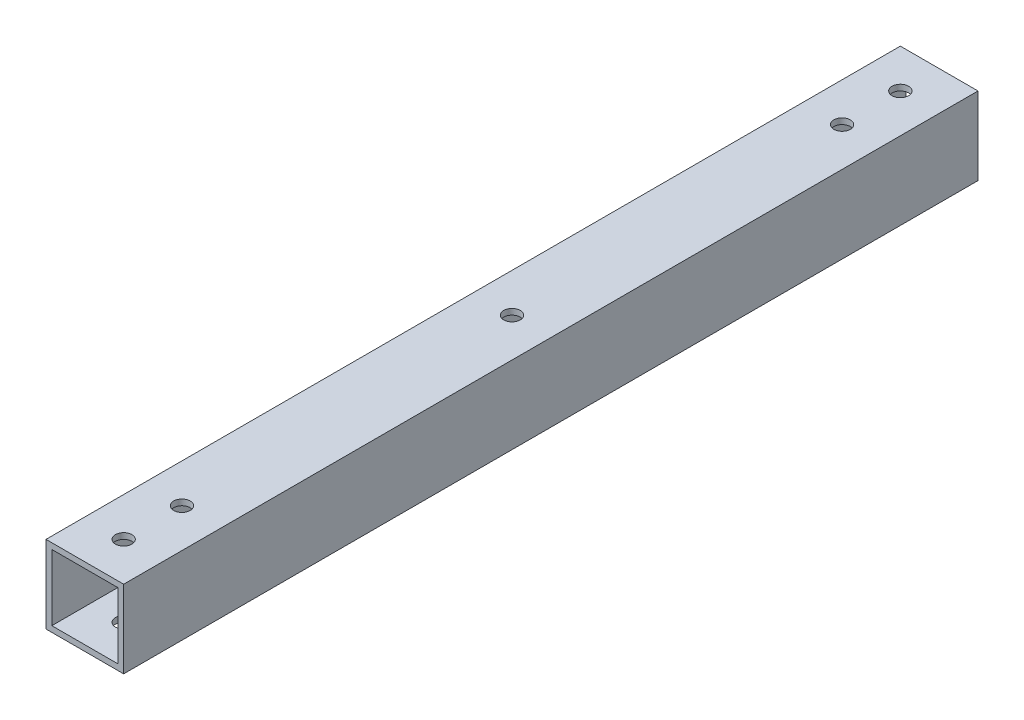
SolidWorks part; units mm, degrees
ref_plane "Front Plane" through (0, 0, 0) normal (0, 0, 1) x (1, 0, 0)
ref_plane "Top Plane" through (0, 0, 0) normal (0, 1, 0) x (1, 0, 0)
ref_plane "Right Plane" through (0, 0, 0) normal (1, 0, 0) x (0, 0, -1)
sketch "Sketch1" plane through (0, 0, 0) normal (0, 0, 1) x (1, 0, 0)
  line L0 (-8.5, -8.5) -> (8.5, -8.5)
  line L1 (-10, -10) -> (10, -10)
  line L2 (-10, -10) -> (-10, 10)
  line L3 (-10, 10) -> (10, 10)
  line L4 (10, -10) -> (10, 10)
  line L5 (-10, -10) -> (10, 10) construction
  line L6 (-10, 10) -> (10, -10) construction
  line L7 (8.5, -8.5) -> (8.5, 8.5)
  line L8 (-8.5, 8.5) -> (8.5, 8.5)
  line L9 (-8.5, -8.5) -> (-8.5, 8.5)
  point P0 (0, 0)
  dimension "D1" = 20
  dimension "D3" = 20
  dimension "D2" = 1.5
extrude "Boss-Extrude1" add sketch "Sketch1" against normal blind 220
sketch "Sketch2" plane through (0, 10, 0) normal (0, 1, 0) x (1, 0, 0)
  line L0 (10, 0) -> (-10, 0) construction
  line L1 (-10, 110) -> (10, 110) construction
  line L2 (-10, 220) -> (-10, 0) construction
  line L3 (10, 220) -> (10, 0) construction
  circle A0 centre (0, 10) radius 2.125
  circle A1 centre (0, 60) radius 2.125 construction
  circle A2 centre (0, 110) radius 2.125
  circle A3 centre (0, 160) radius 2.125 construction
  circle A4 centre (0, 210) radius 2.125
  circle A5 centre (0, 25) radius 2.125
  circle A6 centre (0, 195) radius 2.125
  dimension "D1" = 4.25
  dimension "D5" = 4.25
  dimension "D2" = 10
  dimension "D4" = 50
  dimension "D6" = 15
  dimension "D3" = 5
extrude "Cut-Extrude1" cut sketch "Sketch2" against normal through all
